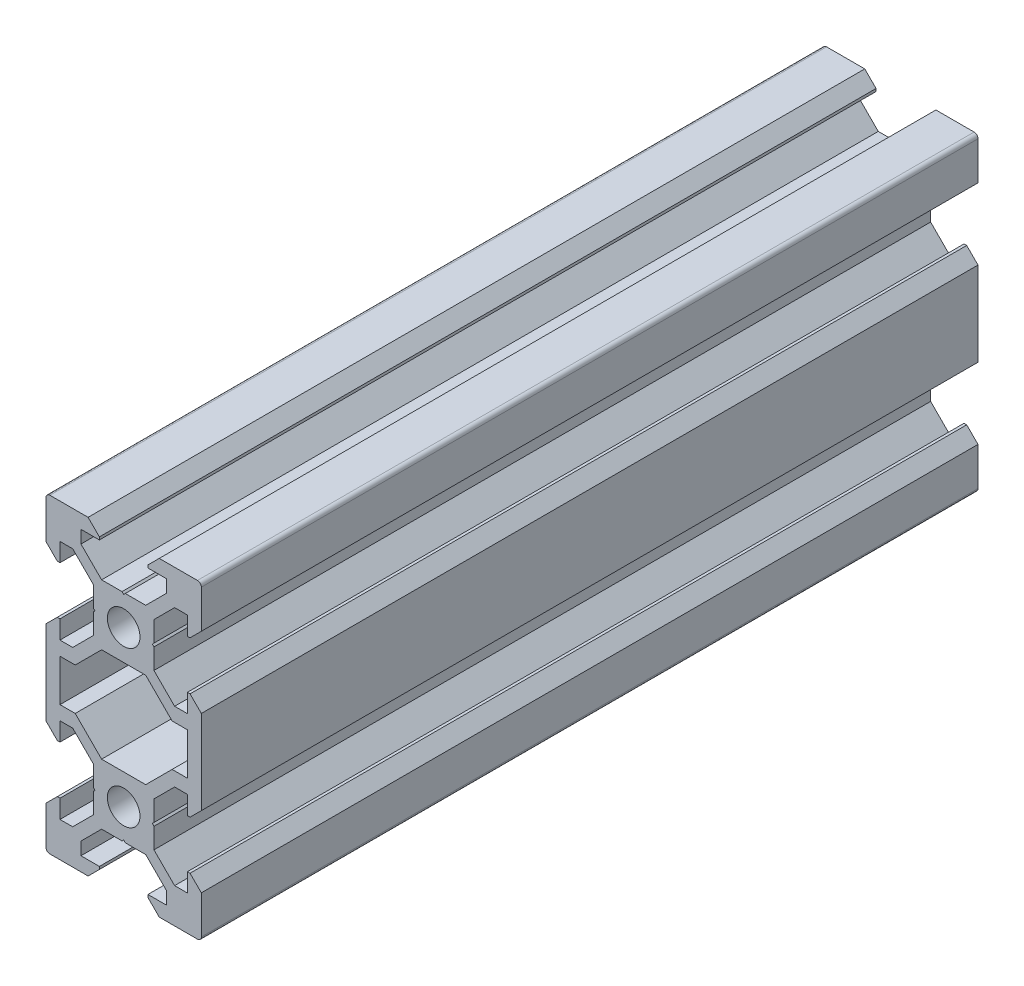
SolidWorks part; units mm, degrees
material "6061-T6 (SS)"
ref_plane "Front Plane" through (0, 0, 0) normal (0, 0, 1) x (1, 0, 0)
ref_plane "Top Plane" through (0, 0, 0) normal (0, 1, 0) x (1, 0, 0)
ref_plane "Right Plane" through (0, 0, 0) normal (1, 0, 0) x (0, 0, -1)
ref_plane "Plane1" through (0, 0, 500) normal (0, 0, 1) x (1, 0, 0)
sketch "Sketch1" plane through (0, 0, 500) normal (0, 0, 1) x (1, 0, 0)
  line L0 (6.5607, 4.5) -> (3.9, 7.1607)
  line L1 (3.9, 7.1607) -> (3.9, 9.79)
  line L2 (3.9, 9.79) -> (3.69, 10)
  line L3 (3.69, 10) -> (3.9, 10.21)
  line L4 (3.9, 10.21) -> (3.9, 12.8393)
  line L5 (3.9, 12.8393) -> (6.5607, 15.5)
  line L6 (6.5607, 15.5) -> (8.2, 15.5)
  line L7 (8.2, 15.5) -> (8.2, 13.125)
  line L8 (8.2, 13.125) -> (8.545, 13.125)
  line L9 (8.545, 13.125) -> (10, 14.58)
  line L10 (10, 14.58) -> (10, 19.5)
  line L11 (9.5, 20) -> (4.58, 20)
  line L12 (4.58, 20) -> (3.125, 18.545)
  line L13 (3.125, 18.545) -> (3.125, 18.2)
  line L14 (3.125, 18.2) -> (5.5, 18.2)
  line L15 (5.5, 18.2) -> (5.5, 16.5607)
  line L16 (5.5, 16.5607) -> (2.8393, 13.9)
  line L17 (2.8393, 13.9) -> (0.21, 13.9)
  line L18 (0.21, 13.9) -> (0, 13.69)
  line L19 (0, 13.69) -> (-0.21, 13.9)
  line L20 (-0.21, 13.9) -> (-2.8393, 13.9)
  line L21 (-2.8393, 13.9) -> (-5.5, 16.5607)
  line L22 (-5.5, 16.5607) -> (-5.5, 18.2)
  line L23 (-5.5, 18.2) -> (-3.125, 18.2)
  line L24 (-3.125, 18.2) -> (-3.125, 18.545)
  line L25 (-3.125, 18.545) -> (-4.58, 20)
  line L26 (-4.58, 20) -> (-9.5, 20)
  line L27 (-10, 19.5) -> (-10, 14.58)
  line L28 (-10, 14.58) -> (-8.545, 13.125)
  line L29 (-8.545, 13.125) -> (-8.2, 13.125)
  line L30 (-8.2, 13.125) -> (-8.2, 15.5)
  line L31 (-8.2, 15.5) -> (-6.5607, 15.5)
  line L32 (-6.5607, 15.5) -> (-3.9, 12.8393)
  line L33 (-3.9, 12.8393) -> (-3.9, 10.21)
  line L34 (-3.9, 10.21) -> (-3.69, 10)
  line L35 (-3.69, 10) -> (-3.9, 9.79)
  line L36 (-3.9, 9.79) -> (-3.9, 7.1607)
  line L37 (-3.9, 7.1607) -> (-6.5607, 4.5)
  line L38 (-6.5607, 4.5) -> (-8.2, 4.5)
  line L39 (-8.2, 4.5) -> (-8.2, 6.875)
  line L40 (-8.2, 6.875) -> (-8.545, 6.875)
  line L41 (-8.545, 6.875) -> (-10, 5.42)
  line L42 (-10, 5.42) -> (-10, -5.42)
  line L43 (-10, -5.42) -> (-8.545, -6.875)
  line L44 (-8.545, -6.875) -> (-8.2, -6.875)
  line L45 (-8.2, -6.875) -> (-8.2, -4.5)
  line L46 (-8.2, -4.5) -> (-6.5607, -4.5)
  line L47 (-6.5607, -4.5) -> (-3.9, -7.1607)
  line L48 (-3.9, -7.1607) -> (-3.9, -9.79)
  line L49 (-3.9, -9.79) -> (-3.69, -10)
  line L50 (-3.69, -10) -> (-3.9, -10.21)
  line L51 (-3.9, -10.21) -> (-3.9, -12.8393)
  line L52 (-3.9, -12.8393) -> (-6.5607, -15.5)
  line L53 (-6.5607, -15.5) -> (-8.2, -15.5)
  line L54 (-8.2, -15.5) -> (-8.2, -13.125)
  line L55 (-8.2, -13.125) -> (-8.545, -13.125)
  line L56 (-8.545, -13.125) -> (-10, -14.58)
  line L57 (-10, -14.58) -> (-10, -19.5)
  line L58 (-9.5, -20) -> (-4.58, -20)
  line L59 (-4.58, -20) -> (-3.125, -18.545)
  line L60 (-3.125, -18.545) -> (-3.125, -18.2)
  line L61 (-3.125, -18.2) -> (-5.5, -18.2)
  line L62 (-5.5, -18.2) -> (-5.5, -16.5607)
  line L63 (-5.5, -16.5607) -> (-2.8393, -13.9)
  line L64 (-2.8393, -13.9) -> (-0.21, -13.9)
  line L65 (-0.21, -13.9) -> (0, -13.69)
  line L66 (0, -13.69) -> (0.21, -13.9)
  line L67 (0.21, -13.9) -> (2.8393, -13.9)
  line L68 (2.8393, -13.9) -> (5.5, -16.5607)
  line L69 (5.5, -16.5607) -> (5.5, -18.2)
  line L70 (5.5, -18.2) -> (3.125, -18.2)
  line L71 (3.125, -18.2) -> (3.125, -18.545)
  line L72 (3.125, -18.545) -> (4.58, -20)
  line L73 (4.58, -20) -> (9.5, -20)
  line L74 (10, -19.5) -> (10, -14.58)
  line L75 (10, -14.58) -> (8.545, -13.125)
  line L76 (8.545, -13.125) -> (8.2, -13.125)
  line L77 (8.2, -13.125) -> (8.2, -15.5)
  line L78 (8.2, -15.5) -> (6.5607, -15.5)
  line L79 (6.5607, -15.5) -> (3.9, -12.8393)
  line L80 (3.9, -12.8393) -> (3.9, -10.21)
  line L81 (3.9, -10.21) -> (3.69, -10)
  line L82 (3.69, -10) -> (3.9, -9.79)
  line L83 (3.9, -9.79) -> (3.9, -7.1607)
  line L84 (3.9, -7.1607) -> (6.5607, -4.5)
  line L85 (6.5607, -4.5) -> (8.2, -4.5)
  line L86 (8.2, -4.5) -> (8.2, -6.875)
  line L87 (8.2, -6.875) -> (8.545, -6.875)
  line L88 (8.545, -6.875) -> (10, -5.42)
  line L89 (10, -5.42) -> (10, 5.42)
  line L90 (10, 5.42) -> (8.545, 6.875)
  line L91 (8.545, 6.875) -> (8.2, 6.875)
  line L92 (8.2, 6.875) -> (8.2, 4.5)
  line L93 (8.2, 4.5) -> (6.5607, 4.5)
  line L94 (2.8393, -6.1) -> (-2.8393, -6.1)
  line L95 (-2.8393, -6.1) -> (-6.2393, -2.7)
  line L96 (-6.2393, -2.7) -> (-8.2, -2.7)
  line L97 (-8.2, -2.7) -> (-8.2, 2.7)
  line L98 (-8.2, 2.7) -> (-6.2393, 2.7)
  line L99 (-6.2393, 2.7) -> (-2.8393, 6.1)
  line L100 (-2.8393, 6.1) -> (2.8393, 6.1)
  line L101 (2.8393, 6.1) -> (6.2393, 2.7)
  line L102 (6.2393, 2.7) -> (8.2, 2.7)
  line L103 (8.2, 2.7) -> (8.2, -2.7)
  line L104 (8.2, -2.7) -> (6.2393, -2.7)
  line L105 (6.2393, -2.7) -> (2.8393, -6.1)
  circle A0 centre (0, 10) radius 2.1
  circle A1 centre (0, -10) radius 2.1
  arc A2 (10, 19.5) -> (9.5, 20) centre (9.5, 19.5) ccw
  arc A3 (-9.5, 20) -> (-10, 19.5) centre (-9.5, 19.5) ccw
  arc A4 (-10, -19.5) -> (-9.5, -20) centre (-9.5, -19.5) ccw
  arc A5 (9.5, -20) -> (10, -19.5) centre (9.5, -19.5) ccw
extrude "Boss-Extrude1" add sketch "Sketch1" against normal blind 100
